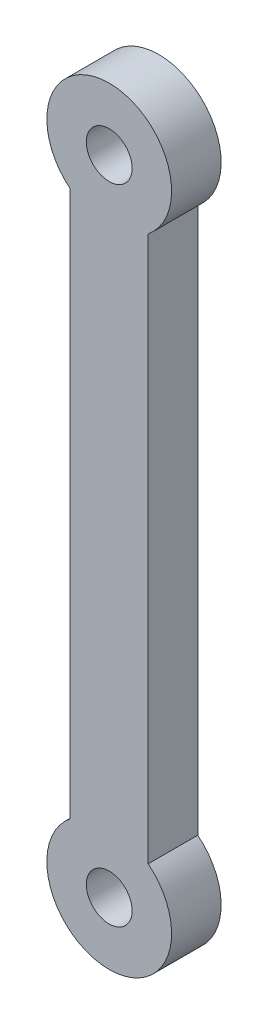
SolidWorks part; units mm, degrees
ref_plane "Front Plane" through (0, 0, 0) normal (0, 0, 1) x (1, 0, 0)
ref_plane "Top Plane" through (0, 0, 0) normal (0, 1, 0) x (1, 0, 0)
ref_plane "Right Plane" through (0, 0, 0) normal (1, 0, 0) x (0, 0, -1)
sketch "Sketch1" plane through (0, 0, 0) normal (0, 0, 1) x (1, 0, 0)
  line L0 (0, 0) -> (0, 59.5848) construction
  line L1 (-2.5, 3.1225) -> (-2.5, 38.1225)
  line L2 (2.5, 3.1225) -> (2.5, 38.1225)
  line L3 (0, 0) -> (1.4406, -0.2928) construction
  line L7 (18.6194, -3.7839) -> (46.0448, -8.7543) construction
  arc A0 (-2.5, 3.1225) -> (2.5621, -3.0718) centre (0, 0) ccw
  arc A1 (2.5, 38.1225) -> (-2.5, 38.1225) centre (0, 41.245) ccw
  arc A3 (3.5578, 1.8281) -> (2.5, 3.1225) centre (0, 0) ccw
  circle A5 centre (0, 41.245) radius 1.47
  circle A6 centre (0, 0) radius 1.47
  arc A7 (3.5578, 1.8281) -> (2.5621, -3.0718) centre (0, 0) cw
  dimension "D2" = 8
  dimension "D4" = 8
  dimension "D5" = 2.94
  dimension "D1" = 5
  dimension "D3" = 35
extrude "Boss-Extrude1" add sketch "Sketch1" along normal blind 3.18
